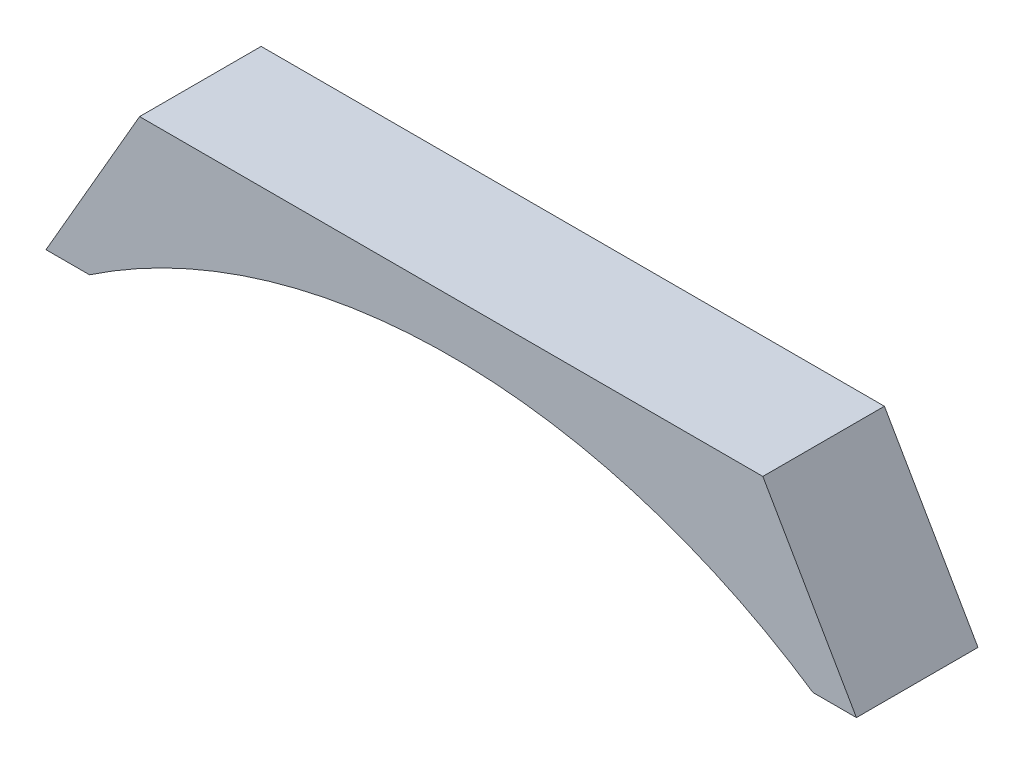
SolidWorks part; units mm, degrees
ref_plane "Front Plane" through (0, 0, 0) normal (0, 0, 1) x (1, 0, 0)
ref_plane "Top Plane" through (0, 0, 0) normal (0, 1, 0) x (1, 0, 0)
ref_plane "Right Plane" through (0, 0, 0) normal (1, 0, 0) x (0, 0, -1)
sketch "Sketch1" plane through (0, 0, 0) normal (0, 0, 1) x (1, 0, 0)
  line L0 (-78.1647, 0) -> (-63.5, 25.4)
  line L1 (-63.5, 25.4) -> (63.5, 25.4)
  line L2 (63.5, 25.4) -> (78.1647, 0)
  line L3 (78.1647, 0) -> (-78.1647, 0)
  point P6 (0, 0)
  dimension "D1" = 25.4
  dimension "D2" = 127
  dimension "D3" = 60
extrude "Boss-Extrude1" add sketch "Sketch1" against normal blind 19.05
sketch "Sketch2" plane through (58.6235, 33.8463, 0) normal (0.866, 0.5, 0) x (0, 0, -1)
  line L1 (-39.3951, 50.4516) -> (80.3801, 50.4516)
  line L2 (-39.3951, 50.4516) -> (-39.3951, -95.1575)
  line L3 (-39.3951, -95.1575) -> (80.3801, -95.1575)
  line L4 (80.3801, 50.4516) -> (80.3801, -95.1575)
extrude "Cut-Extrude1" cut sketch "Sketch2" against normal blind 25.4
sketch "Sketch3" plane through (0, 0, 0) normal (0, 0, 1) x (1, 0, 0)
  line L0 (-14.6647, 0) -> (-14.6647, -84.3146) construction
  line L1 (-78.1647, 0) -> (48.8353, 0) construction
  circle A0 centre (-14.6647, -84.3146) radius 101.6
  dimension "D1" = 203.2
extrude "Cut-Extrude2" cut sketch "Sketch3" against normal through all
